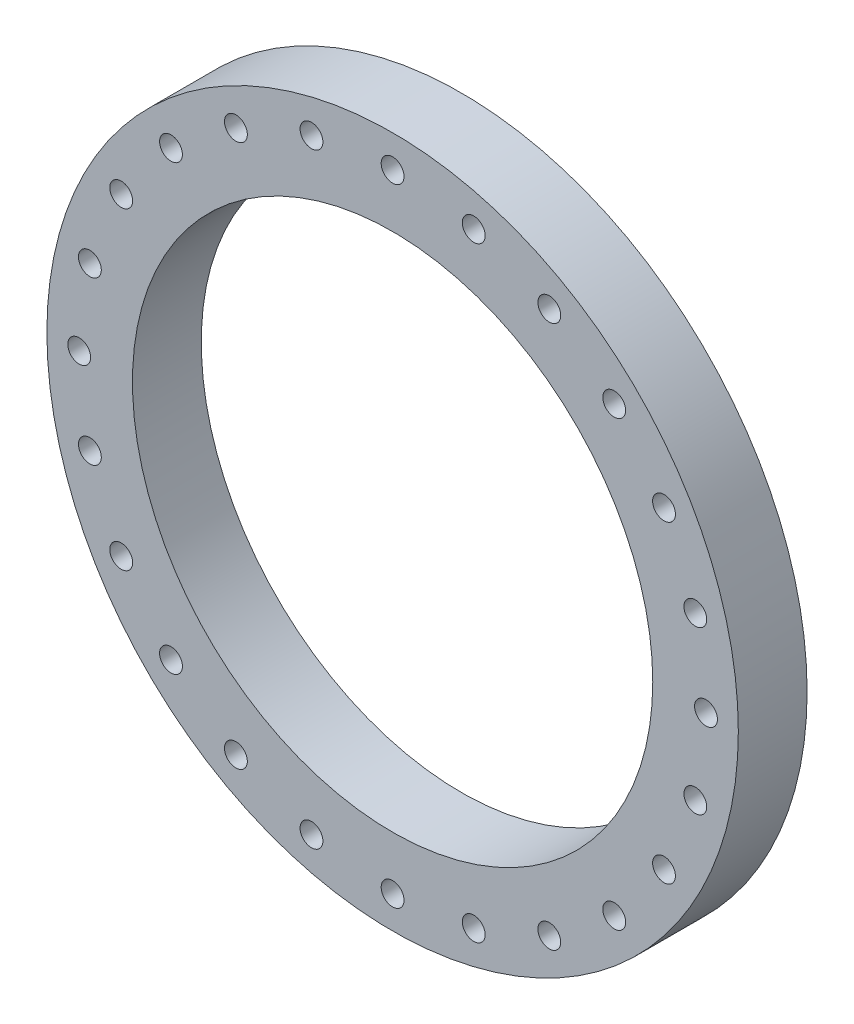
SolidWorks part; units mm, degrees
material "PE Low/Medium Density"
ref_plane "Front Plane" through (0, 0, 0) normal (0, 0, 1) x (1, 0, 0)
ref_plane "Top Plane" through (0, 0, 0) normal (0, 1, 0) x (1, 0, 0)
ref_plane "Right Plane" through (0, 0, 0) normal (1, 0, 0) x (0, 0, -1)
sketch "Sketch1" plane through (0, 0, 0) normal (0, 0, 1) x (1, 0, 0)
  circle A0 centre (0, 0) radius 63.8302
  circle A1 centre (0, 0) radius 48.0314
  dimension "D1" = 15.7988
  dimension "D2" = 127.6604
extrude "Extrude1" add sketch "Sketch1" along normal blind 12.7
sketch "Sketch2" plane through (0, 0, 12.7) normal (0, 0, 1) x (1, 0, 0)
  line L0 (0, 0) -> (0, 57.8612) construction
  line L1 (0, 57.8612) -> (0, 63.8302) construction
  circle A0 centre (0, 0) radius 63.8302 construction
  dimension "D1" = 5.969
hole_wizard "#19 (0.166) Diameter Hole1" positions "3DSketch1" profile "Sketch3" hole size "#19" standard "Ansi Inch" end condition through all
sketch3d "3DSketch1"
  point P0 (0, 57.8612, 12.7)
sketch "Sketch3" plane through (0, 57.8612, 12.7) normal (1, 0, 0) x (0, -1, 0)
  line L0 (0, 0) -> (0, 12.7)
  line L1 (0, 12.7) -> (2.1082, 12.7)
  line L2 (2.1082, 12.7) -> (2.1082, 0)
  line L5 (2.1082, 0) -> (0, 0)
  line L11 (0, -6.35) -> (0, 107.95) construction
  dimension "Thru Hole Dia." = 4.2164
  dimension "Thru Hole Depth" = 12.7
pattern_circular "CirPattern1" count 24 over 360 about axis through (0, 0, 0) along (0, 0, 1) of "#19 (0.166) Diameter Hole1"
